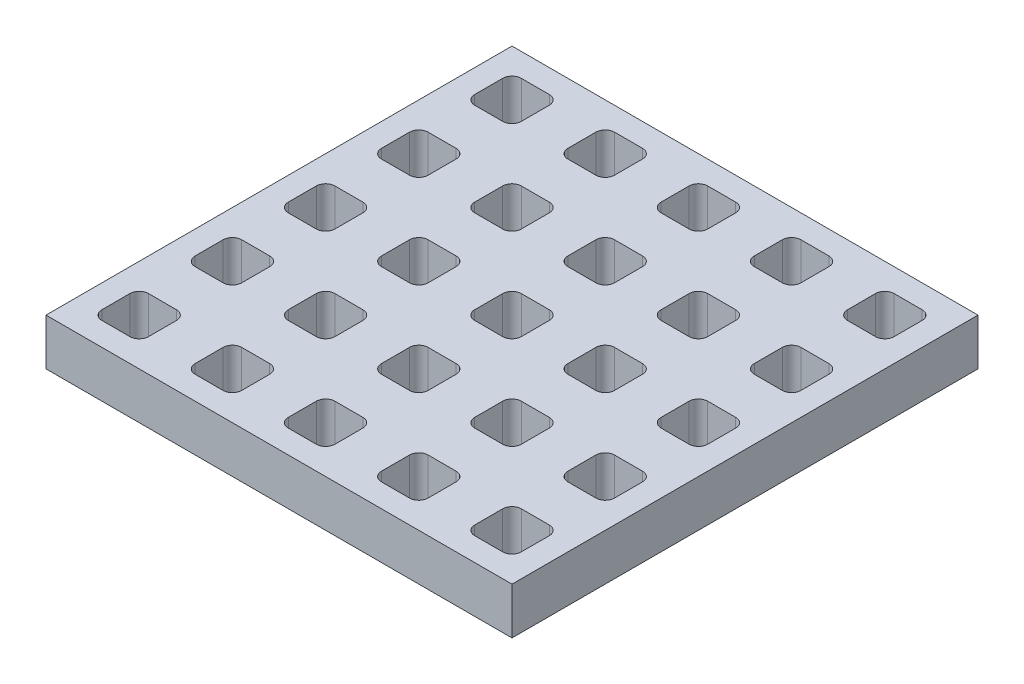
SolidWorks part; units mm, degrees
ref_plane "Alzado" through (0, 0, 0) normal (0, 0, 1) x (1, 0, 0)
ref_plane "Planta" through (0, 0, 0) normal (0, 1, 0) x (1, 0, 0)
ref_plane "Vista lateral" through (0, 0, 0) normal (1, 0, 0) x (0, 0, -1)
sketch "Croquis1" plane through (0, 0, 0) normal (0, 1, 0) x (1, 0, 0)
  line L1 (-50, 50) -> (50, 50)
  line L2 (-50, 50) -> (-50, -50)
  line L3 (-50, -50) -> (50, -50)
  line L4 (50, 50) -> (50, -50)
  line L5 (-50, 50) -> (50, -50) construction
  line L6 (-50, -50) -> (50, 50) construction
  point P0 (0, 0)
  dimension "D1" = 100
  dimension "D2" = 100
extrude "Saliente-Extruir1" add sketch "Croquis1" along normal blind 10
sketch "Croquis2" plane through (0, 10, 0) normal (0, 1, 0) x (1, 0, 0)
  line L0 (50, 50) -> (-50, 50) construction
  line L1 (-45, 45) -> (-35, 45)
  line L2 (-45, 45) -> (-45, 35)
  line L3 (-45, 35) -> (-35, 35)
  line L4 (-35, 45) -> (-35, 35)
  line L5 (-50, 50) -> (-50, -50) construction
  dimension "D1" = 10
  dimension "D2" = 10
  dimension "D3" = 5
  dimension "D4" = 5
extrude "Cortar-Extruir1" cut sketch "Croquis2" against normal through all
fillet "Redondeo1" radius 2 4 edges at (-45, 5, -35) (-35, 5, -35) (-35, 5, -45) (-45, 5, -45)
pattern_linear "MatrizL1" count 5 spacing 20 along (1, 0, 0) count 5 spacing 20 along (0, 0, 1) of "Cortar-Extruir1", "Redondeo1"
